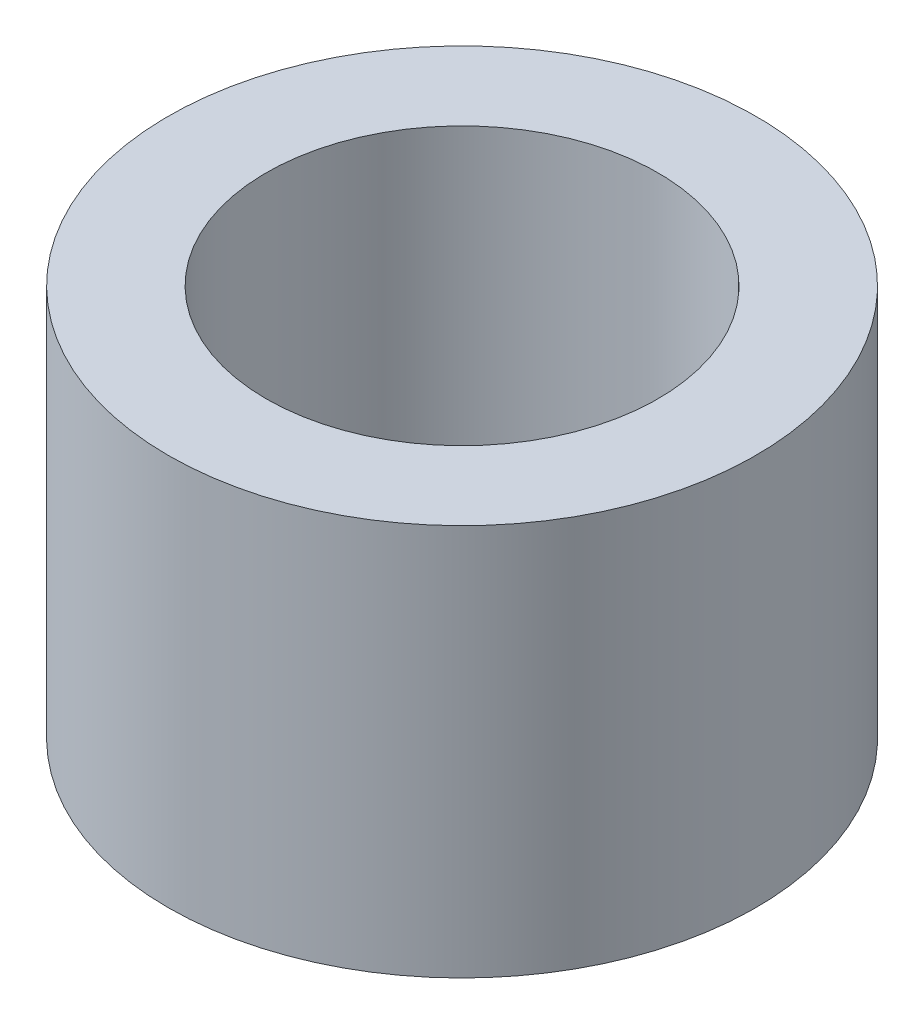
SolidWorks part; units mm, degrees
material "Силикон"
ref_plane "Спереди" through (0, 0, 0) normal (0, 0, 1) x (1, 0, 0)
ref_plane "Сверху" through (0, 0, 0) normal (0, 1, 0) x (1, 0, 0)
ref_plane "Справа" through (0, 0, 0) normal (1, 0, 0) x (0, 0, -1)
other "Configuration Table"
sketch "Эскиз1" plane through (0, 0, 0) normal (0, 1, 0) x (1, 0, 0)
  circle A0 centre (0, 0) radius 4
  circle A1 centre (0, 0) radius 6
  dimension "D1" = 8
  dimension "D2" = 12
extrude "Бобышка-Вытянуть1" add sketch "Эскиз1" along normal blind 8
